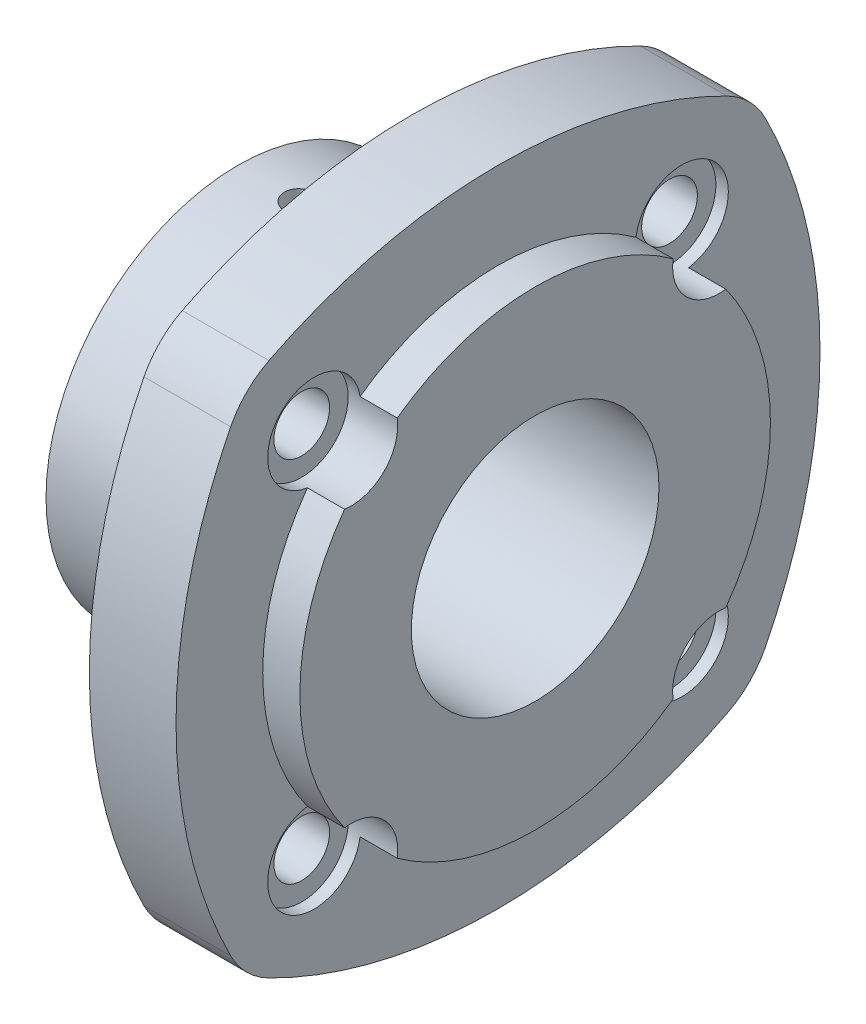
SolidWorks part; units mm, degrees
ref_plane "前基準面" through (0, 0, 0) normal (0, 0, 1) x (1, 0, 0)
ref_plane "上基準面" through (0, 0, 0) normal (0, 1, 0) x (1, 0, 0)
ref_plane "右基準面" through (0, 0, 0) normal (1, 0, 0) x (0, 0, -1)
sketch "草圖1" plane through (0, 0, 0) normal (1, 0, 0) x (0, 0, -1)
  line L0 (0, -24.5802) -> (0, 55.4954) construction
  line L1 (-37.0552, 0) -> (54.1702, 0) construction
  arc A0 (41.0089, 41.0089) -> (-41.0089, 41.0089) centre (0, -30) ccw
  arc A1 (41.0089, 41.0089) -> (41.0089, -41.0089) centre (-30, 0) cw
  arc A2 (-41.0089, 41.0089) -> (-41.0089, -41.0089) centre (30, 0) ccw
  arc A3 (41.0089, -41.0089) -> (-41.0089, -41.0089) centre (0, 30) cw
  dimension "D1" = 82
  dimension "D2" = 82
  dimension "D3" = 104
  dimension "D4" = 104
extrude "伸長1" add sketch "草圖1" along normal blind 14
sketch "草圖2" plane through (14, 0, 0) normal (1, 0, 0) x (0, 0, -1)
  circle A0 centre (0, 0) radius 38
  dimension "D1" = 76
extrude "伸長2" add sketch "草圖2" along normal blind 6
sketch "草圖3" plane through (0, 0, 0) normal (-1, 0, 0) x (0, 0, 1)
  circle A0 centre (0, 0) radius 31
  dimension "D1" = 62
extrude "伸長3" add sketch "草圖3" along normal blind 28
sketch "草圖4" plane through (20, 0, 0) normal (1, 0, 0) x (0, 0, -1)
  circle A0 centre (0, 0) radius 20
  dimension "D1" = 40
extrude "伸長4" cut sketch "草圖4" against normal through all
sketch "草圖5" plane through (0, 0, 0) normal (0, 1, 0) x (1, 0, 0)
  circle A0 centre (-18, 0) radius 2.5
  dimension "D1" = 18
  dimension "D2" = 5
extrude "伸長5" cut sketch "草圖5" along normal through all
hole_wizard "M8 六角承窩頭蓋螺釘的柱孔1" positions "草圖7" profile "草圖6" counterbore size "M8" standard "ISO" end condition through all
sketch "草圖7" plane through (20, 0, 0) normal (1, 0, 0) x (0, 0, -1)
  line L1 (0, 0) -> (42, 0) construction
  line L2 (0, 0) -> (0, 42) construction
  circle A1 centre (0, 0) radius 42 construction
  point P0 (29.6985, 29.6985)
  point P23 (29.6985, -29.6985)
  point P25 (-29.6985, 29.6985)
  point P26 (-29.6985, -29.6985)
  dimension "D1" = 84
  dimension "D2" = 45
sketch "草圖6" plane through (20, 29.6985, -29.6985) normal (0, 1, 0) x (0, 0, -1)
  line L0 (0, 0) -> (0, 48)
  line L1 (0, 48) -> (4.5, 48)
  line L3 (4.5, 48) -> (4.5, 8)
  line L4 (4.5, 8) -> (7.5, 8)
  line L5 (7.5, 8) -> (7.5, 0)
  line L7 (7.5, 0) -> (0, 0)
  line L11 (0, -6.35) -> (0, 107.95) construction
  dimension "貫穿孔直徑" = 9
  dimension "貫穿孔深度" = 48
  dimension "柱孔直徑" = 15
  dimension "柱孔深度" = 8
fillet "圓角1" radius 14 4 edges at (7, -41.0089, -41.0089) (7, -41.0089, 41.0089) (7, 41.0089, -41.0089) (7, 41.0089, 41.0089)
